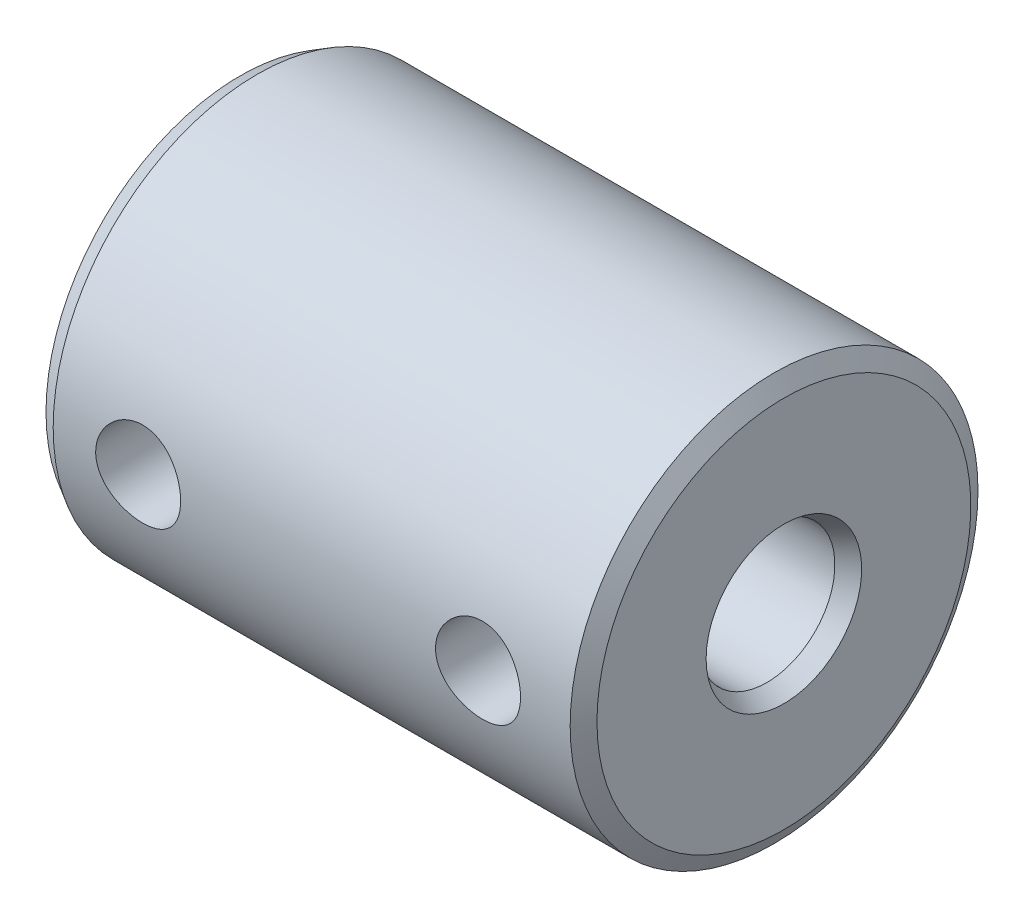
SolidWorks part; units mm, degrees
ref_plane "Plan de face" through (0, 0, 0) normal (0, 0, 1) x (1, 0, 0)
ref_plane "Plan de dessus" through (0, 0, 0) normal (0, 1, 0) x (1, 0, 0)
ref_plane "Plan de droite" through (0, 0, 0) normal (1, 0, 0) x (0, 0, -1)
sketch "Esquisse1" plane through (0, 0, 0) normal (0, 0, 1) x (1, 0, 0)
  line L0 (0, 0) -> (42.0718, 0) construction
  line L1 (0, 3) -> (0, 6)
  line L2 (0, 6) -> (16, 6)
  line L3 (16, 6) -> (16, 2)
  line L4 (16, 2) -> (8, 2)
  line L5 (8, 2) -> (8, 3)
  line L6 (8, 3) -> (0, 3)
  dimension "D1" = 4
  dimension "D2" = 6
  dimension "D3" = 8
  dimension "D4" = 16
  dimension "D5" = 12
revolve "Révolution1" add sketch "Esquisse1" angle 360 about L0
chamfer "Chanfrein1" distance 0.5 angle 30 4 edges at (0, 0, 3) (0, 0, 6) (16, 0, 6) (16, 0, 2)
hole_wizard "Trou taraudé M31" positions "Esquisse3" profile "Esquisse2" tap size "M3" standard "ISO"
sketch "Esquisse3" plane through (0, 0, 0) normal (0, 0, 1) x (1, 0, 0)
  line L0 (0, 0) -> (16, 0) construction
  line L1 (16, -5.5) -> (16, 5.5) construction
  line L2 (0, 5.7113) -> (0, -5.7113) construction
  point P0 (3, 0)
  point P10 (13, 0)
  dimension "D1" = 3
  dimension "D2" = 3
sketch "Esquisse2" plane through (3, 0, 0) normal (1, 0, 0) x (0, 1, 0)
  line L0 (0, 0) -> (0, 6)
  line L1 (0, 6) -> (1.25, 6)
  line L2 (1.25, 6) -> (1.25, 0)
  line L5 (1.25, 0) -> (0, 0)
  line L11 (0, -6.35) -> (0, 107.95) construction
  dimension "Diamètre du trou pour taraudage jusqu'au prochain" = 2.5
  dimension "Profondeur du trou pour taraudage jusqu'au prochain" = 6
cosmetic thread "Filetage de perçage1" parameters "D2"=3
cosmetic thread "Filetage de perçage2" parameters "D2"=3
